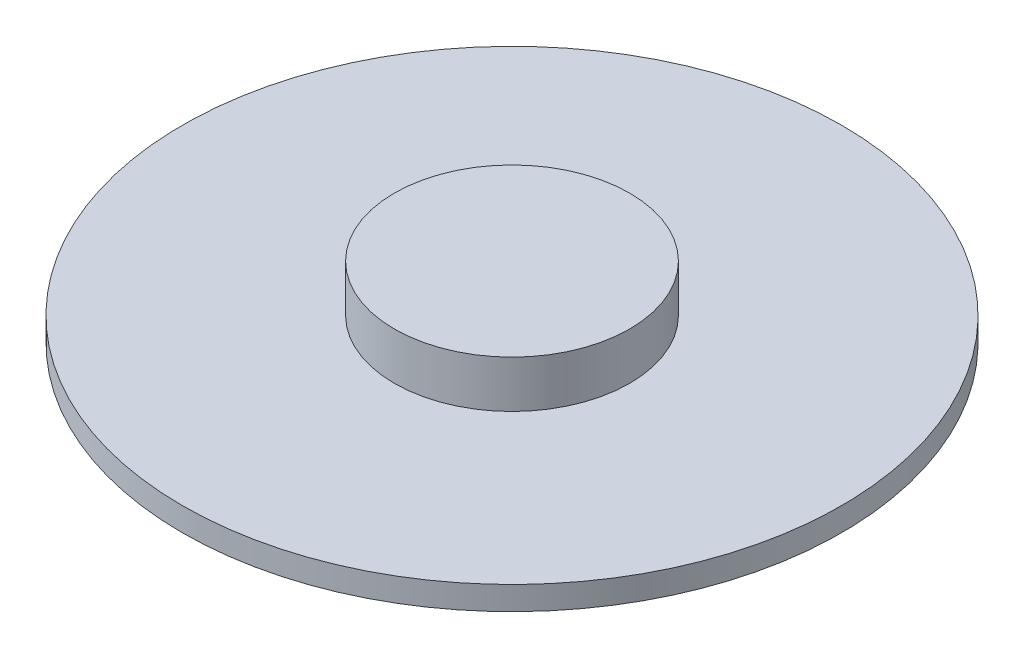
SolidWorks part; units mm, degrees
ref_plane "Alzado" through (0, 0, 0) normal (0, 0, 1) x (1, 0, 0)
ref_plane "Planta" through (0, 0, 0) normal (0, 1, 0) x (1, 0, 0)
ref_plane "Vista lateral" through (0, 0, 0) normal (1, 0, 0) x (0, 0, -1)
sketch "Croquis1" plane through (0, 0, 0) normal (0, 1, 0) x (1, 0, 0)
  circle A0 centre (0, 0) radius 70
  dimension "D1" = 140
extrude "Saliente-Extruir1" add sketch "Croquis1" along normal blind 5
sketch "Croquis8" plane through (0, 5, 0) normal (0, 1, 0) x (1, 0, 0)
  circle A0 centre (0, 0) radius 25
extrude "Saliente-Extruir2" add sketch "Croquis8" along normal blind 10
